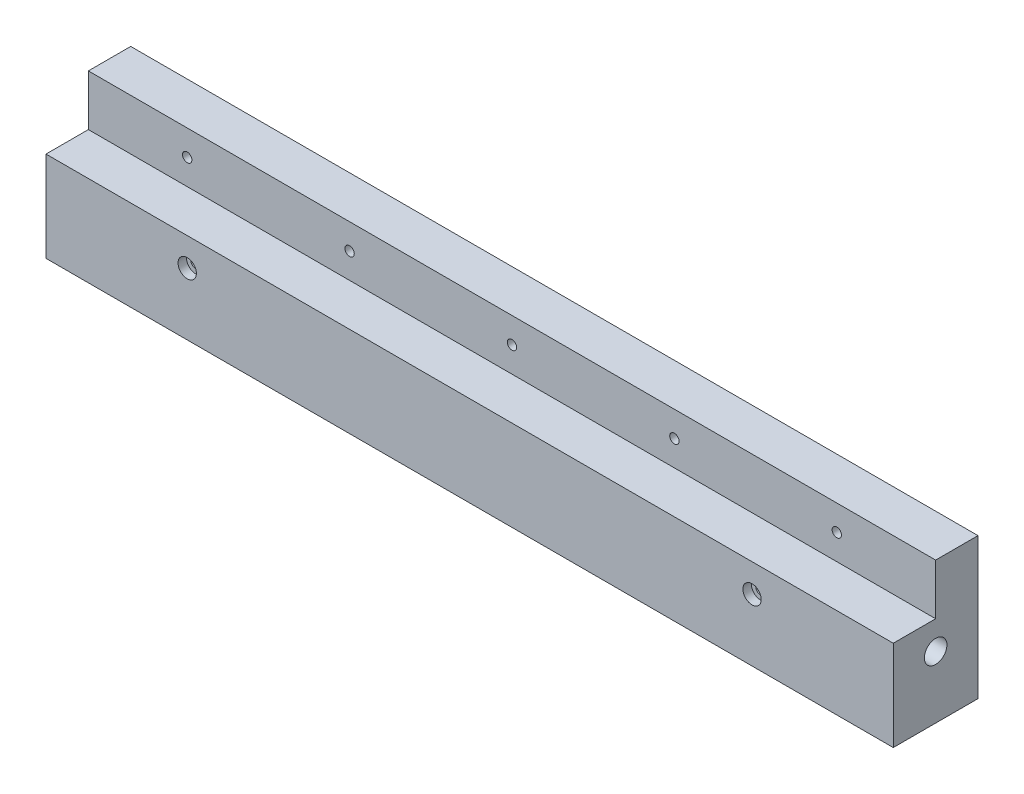
SolidWorks part; units mm, degrees
ref_plane "Front" through (0, 0, 0) normal (0, 0, 1) x (1, 0, 0)
ref_plane "Top" through (0, 0, 0) normal (0, 1, 0) x (1, 0, 0)
ref_plane "Right" through (0, 0, 0) normal (1, 0, 0) x (0, 0, -1)
sketch "Sketch1" plane through (0, 0, 0) normal (1, 0, 0) x (0, 0, -1)
  line L1 (0, 0) -> (-30, 0)
  line L2 (0, 0) -> (0, 32)
  line L3 (0, 32) -> (-30, 32)
  line L4 (-30, 0) -> (-30, 32)
  dimension "D1" = 30
  dimension "D2" = 32
extrude "Boss-Extrude1" add sketch "Sketch1" along normal mid plane 300
sketch "Sketch2" plane through (0, 0, 0) normal (1, 0, 0) x (0, 0, -1)
  line L0 (0, 32) -> (-30, 32) construction
  line L1 (0, 32) -> (-15, 32)
  line L2 (-15, 32) -> (-15, 50)
  line L3 (-15, 50) -> (0, 50)
  line L4 (0, 50) -> (0, 32)
  line L6 (0, 0) -> (0, 32) construction
  dimension "D1" = 15
  dimension "D3" = 18
extrude "Cut-Extrude1" add sketch "Sketch2" along normal up to surface and the other way up to surface up to face at (150, 16, 15) other way up to face at (-150, 16, 15)
sketch "Sketch3" plane through (0, 0, 0) normal (1, 0, 0) x (0, 0, -1)
  circle A0 centre (-15, 22) radius 4
  dimension "D1" = 8
  dimension "D2" = 15
  dimension "D3" = 22
extrude "Cut-Extrude2" cut sketch "Sketch3" against normal through all and the other way through all
hole_wizard "CBORE for M3 Socket Head Cap Screw1" positions "Sketch4" profile "Sketch5" counterbore size "M3" standard "JIS" end condition through all
sketch "Sketch4" plane through (0, 0, 30) normal (0, 0, 1) x (1, 0, 0)
  line L1 (150, 0) -> (-150, 0) construction
  line L3 (0, 41.7541) -> (0, -14.6281) construction
  point P0 (100, 22)
  point P1 (-100, 22)
  dimension "D1" = 200
  dimension "D3" = 22
sketch "Sketch5" plane through (100, 22, 30) normal (1, 0, 0) x (0, -1, 0)
  line L0 (0, 0) -> (0, 30)
  line L1 (0, 30) -> (1.7, 30)
  line L3 (1.7, 30) -> (1.7, 3)
  line L4 (1.7, 3) -> (3.25, 3)
  line L5 (3.25, 3) -> (3.25, 0)
  line L7 (3.25, 0) -> (0, 0)
  line L11 (0, -6.35) -> (0, 107.95) construction
  dimension "通し穴の直径" = 3.4
  dimension "通し穴の深さ" = 30
  dimension "座ぐり穴の直径" = 6.5
  dimension "座ぐり穴の深さ" = 3
hole_wizard "M4x0.7 Tapped Hole1" positions "Sketch6" profile "Sketch7" tap size "M4x0.7" standard "JIS" end condition through all
sketch "Sketch6" plane through (0, 0, 15) normal (0, 0, 1) x (1, 0, 0)
  line L0 (0, 64.5556) -> (0, -17.5637) construction
  line L2 (150, 0) -> (-150, 0) construction
  point P0 (115, 41)
  point P1 (57.5, 41)
  point P3 (0, 41)
  point P5 (-57.5, 41)
  point P7 (-115, 41)
  dimension "D1" = 57.5
  dimension "D2" = 57.5
  dimension "D3" = 57.5
  dimension "D4" = 57.5
  dimension "D5" = 41
sketch "Sketch7" plane through (115, 41, 15) normal (1, 0, 0) x (0, -1, 0)
  line L0 (0, 0) -> (0, 15)
  line L1 (0, 15) -> (1.65, 15)
  line L2 (1.65, 15) -> (1.65, 0)
  line L5 (1.65, 0) -> (0, 0)
  line L11 (0, -6.35) -> (0, 107.95) construction
  dimension "次ｻｰﾌｪｽまでのねじ下穴ﾄﾞﾘﾙ直径" = 3.3
  dimension "次ｻｰﾌｪｽまでのねじ下穴ﾄﾞﾘﾙの深さ" = 15
cosmetic thread "Hole Thread1" parameters "D2"=4
cosmetic thread "Hole Thread2" parameters "D2"=4
cosmetic thread "Hole Thread3" parameters "D2"=4
cosmetic thread "Hole Thread4" parameters "D2"=4
cosmetic thread "Hole Thread5" parameters "D2"=4
hole_wizard "M5x0.8 Tapped Hole1" positions "Sketch8" profile "Sketch9" tap size "M5x0.8" standard "JIS"
sketch "Sketch8" plane through (0, 0, 0) normal (0, -1, 0) x (1, 0, 0)
  line L0 (0, 44.3973) -> (0, -19.8245) construction
  line L2 (150, 0) -> (-150, 0) construction
  line L3 (150, 30) -> (-150, 30) construction
  point P0 (-80, 24)
  point P1 (-80, 6)
  point P3 (80, 6)
  point P5 (80, 24)
  dimension "D1" = 160
  dimension "D2" = 6
  dimension "D3" = 18
  dimension "D4" = 6
sketch "Sketch9" plane through (-80, 0, 24) normal (1, 0, 0) x (0, 0, -1)
  line L0 (0, 0) -> (0, 15.2618)
  line L1 (0, 15.2618) -> (2.1, 14)
  line L2 (2.1, 14) -> (2.1, 0)
  line L5 (2.1, 0) -> (0, 0)
  line L10 (0, 15.2618) -> (-2.1, 14) construction
  line L11 (0, -6.35) -> (0, 107.95) construction
  dimension "ねじ下穴ﾄﾞﾘﾙ直径" = 4.2
  dimension "ねじ下穴ﾄﾞﾘﾙの深さ" = 14
  dimension "ﾄﾞﾘﾙ角度" = 118
cosmetic thread "Hole Thread6" parameters "D1"=10, "D2"=5
cosmetic thread "Hole Thread7" parameters "D1"=10, "D2"=5
cosmetic thread "Hole Thread8" parameters "D1"=10, "D2"=5
cosmetic thread "Hole Thread9" parameters "D1"=10, "D2"=5
